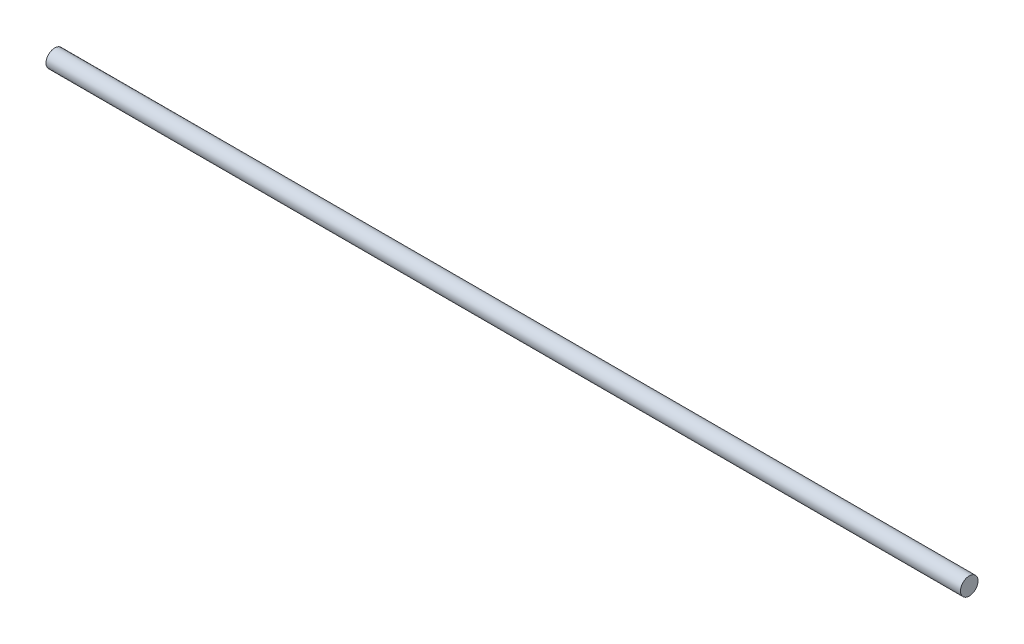
SolidWorks part; units mm, degrees
material "Stainless Steel (ferritic)"
ref_plane "Front Plane" through (0, 0, 0) normal (0, 0, 1) x (1, 0, 0)
ref_plane "Top Plane" through (0, 0, 0) normal (0, 1, 0) x (1, 0, 0)
ref_plane "Right Plane" through (0, 0, 0) normal (1, 0, 0) x (0, 0, -1)
sketch "Sketch1" plane through (0, 0, 0) normal (1, 0, 0) x (0, 0, -1)
  circle A0 centre (0, 0) radius 1.5
  dimension "D1" = 3
extrude "Boss-Extrude1" add sketch "Sketch1" along normal blind 156.49 contours A0
